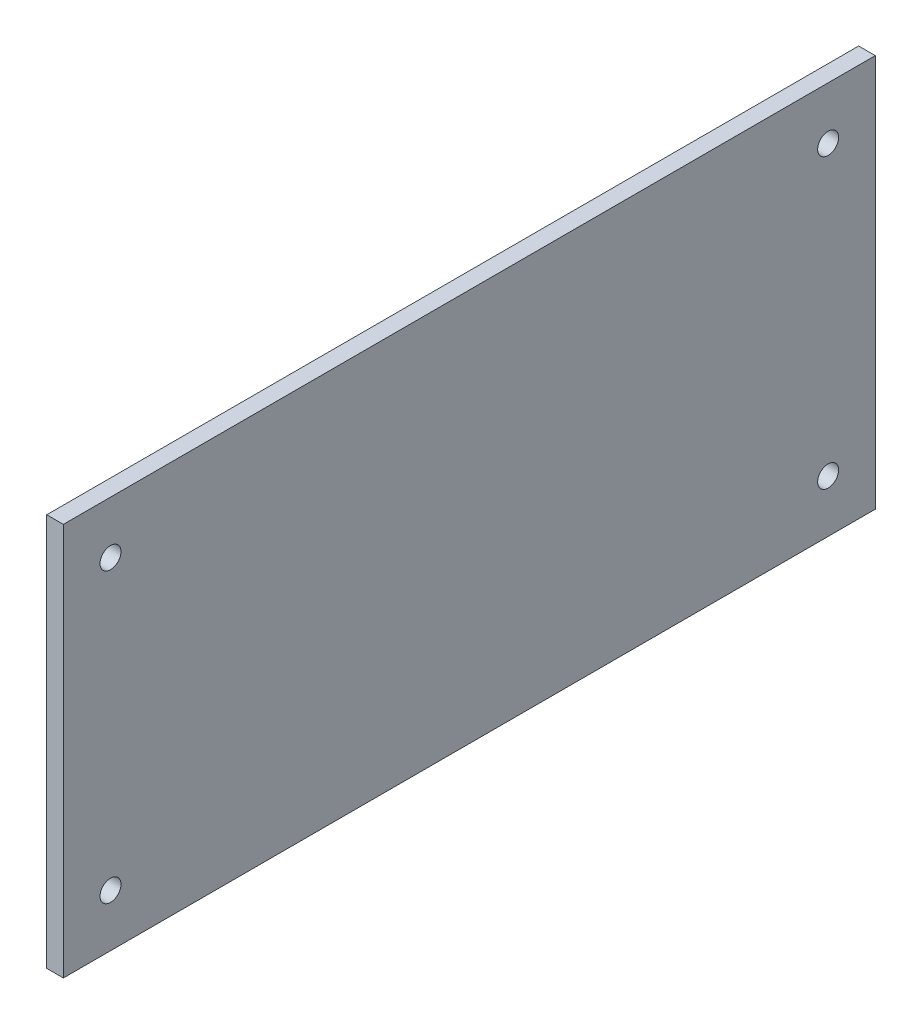
SolidWorks part; units mm, degrees
ref_plane "Front Plane" through (0, 0, 0) normal (0, 0, 1) x (1, 0, 0)
ref_plane "Top Plane" through (0, 0, 0) normal (0, 1, 0) x (1, 0, 0)
ref_plane "Right Plane" through (0, 0, 0) normal (1, 0, 0) x (0, 0, -1)
sketch "Sketch3" plane through (0, 0, 0) normal (1, 0, 0) x (0, 0, -1)
  line L0 (9, 10) -> (146, 10) construction
  line L1 (0, 0) -> (155, 0)
  line L2 (0, 0) -> (0, 75)
  line L3 (0, 75) -> (155, 75)
  line L4 (155, 0) -> (155, 75)
  line L5 (146, 10) -> (146, 65) construction
  line L6 (146, 65) -> (9, 65) construction
  line L7 (9, 65) -> (9, 10) construction
  circle A0 centre (9, 10) radius 2
  circle A1 centre (146, 10) radius 2
  circle A2 centre (146, 65) radius 2
  circle A3 centre (9, 65) radius 2
  point P13 (12.8094, 58.4488)
  dimension "D7" = 4
  dimension "D1" = 10
  dimension "D2" = 75
  dimension "D3" = 155
  dimension "D4" = 9
  dimension "D5" = 9
  dimension "D6" = 10
extrude "Boss-Extrude1" add sketch "Sketch3" along normal blind 3.175
